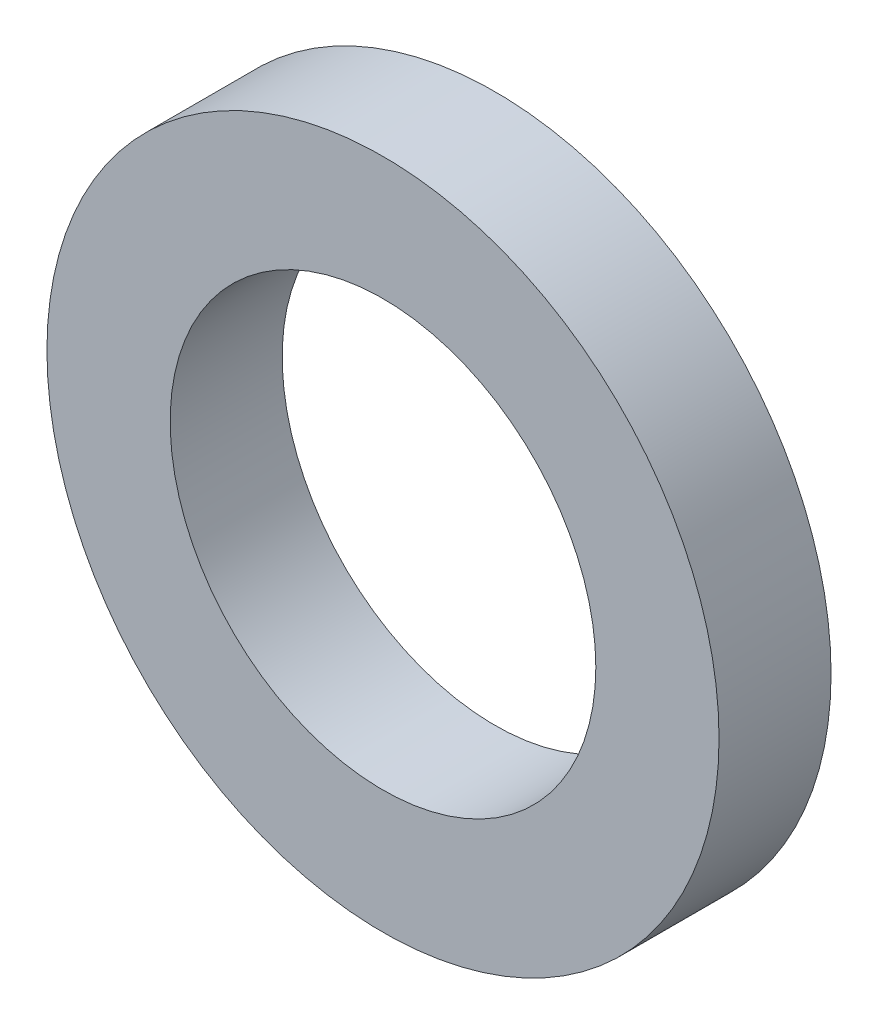
SolidWorks part; units mm, degrees
ref_plane "Ön Düzlem" through (0, 0, 0) normal (0, 0, 1) x (1, 0, 0)
ref_plane "Üst Düzlem" through (0, 0, 0) normal (0, 1, 0) x (1, 0, 0)
ref_plane "Sağ Düzlem" through (0, 0, 0) normal (1, 0, 0) x (0, 0, -1)
sketch "Sketch1" plane through (0, 0, 0) normal (0, 0, 1) x (1, 0, 0)
  circle A0 centre (0, 0) radius 3
  circle A1 centre (0, 0) radius 1.9
extrude "Boss-Extrude1" add sketch "Sketch1" along normal blind 1
scale "Scale1" scale about centroid uniform scaling yes scale factor 1.5
